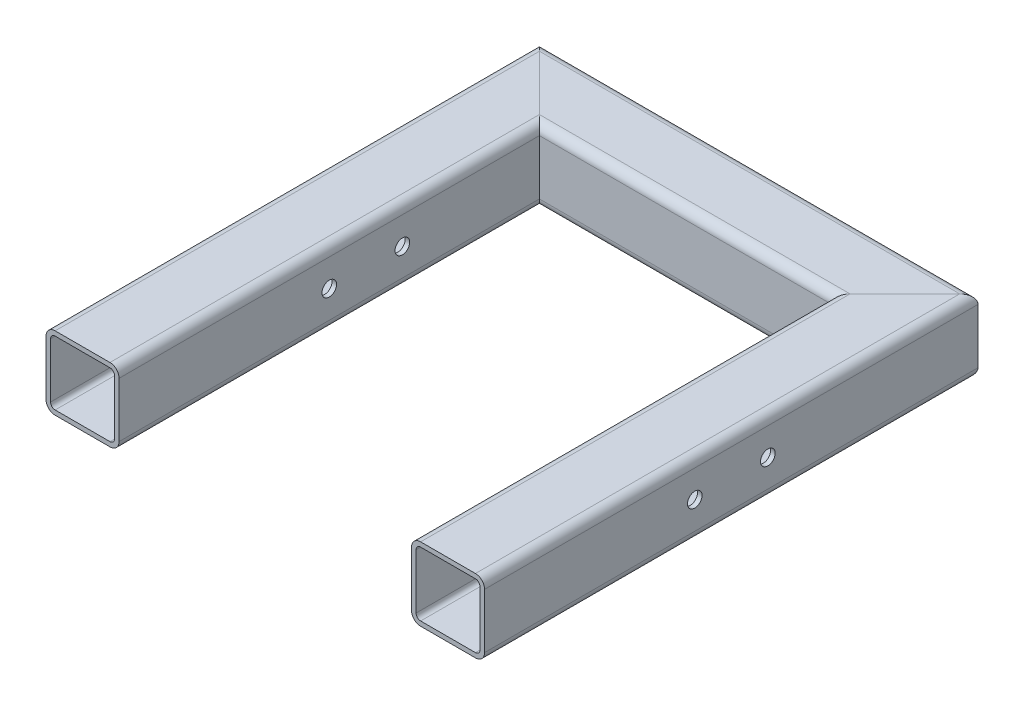
SolidWorks part; units mm, degrees
material "Chrome Stainless Steel"
ref_plane "Front Plane" through (0, 0, 0) normal (0, 0, 1) x (1, 0, 0)
ref_plane "Top Plane" through (0, 0, 0) normal (0, 1, 0) x (1, 0, 0)
ref_plane "Right Plane" through (0, 0, 0) normal (1, 0, 0) x (0, 0, -1)
sketch3d "3DSketch1"
  line L0 (0, 0, 0) -> (0, 0, -500)
  line L1 (0, 0, -500) -> (400, 0, -500)
  line L2 (400, 0, -500) -> (400, 0, 0)
  dimension "D1" = 400
  dimension "D2" = 500
  dimension "D3" = 500
other "Square tube 80 X 80 X 5(1)"
ref_plane "Plane1" through (0, 0, 0) normal (0, 0, -1) x (1, 0, 0)
sketch "Sketch1" plane through (0, 0, 0) normal (0, 0, -1) x (1, 0, 0)
  line L0 (-30, -35) -> (30, -35)
  line L1 (-35, -30) -> (-35, 30)
  line L2 (30, 35) -> (-30, 35)
  line L3 (35, 30) -> (35, -30)
  line L4 (-30, -40) -> (30, -40)
  line L5 (-40, -30) -> (-40, 30)
  line L6 (30, 40) -> (-30, 40)
  line L7 (40, 30) -> (40, -30)
  arc A0 (40, 30) -> (30, 40) centre (30, 30) ccw
  arc A1 (30, -40) -> (40, -30) centre (30, -30) ccw
  arc A2 (-40, -30) -> (-30, -40) centre (-30, -30) ccw
  arc A3 (-30, 40) -> (-40, 30) centre (-30, 30) ccw
  arc A4 (-30, 35) -> (-35, 30) centre (-30, 30) ccw
  arc A5 (35, 30) -> (30, 35) centre (30, 30) ccw
  arc A6 (30, -35) -> (35, -30) centre (30, -30) ccw
  arc A7 (-35, -30) -> (-30, -35) centre (-30, -30) ccw
  point P0 (-40, 0)
  point P1 (40, 0)
  point P2 (0, 40)
  point P3 (0, -40)
  point P4 (0, 0)
  point P5 (-40, -40)
  point P6 (40, -40)
  point P7 (40, 40)
  point P8 (-40, 40)
  point P33 (0, 0)
  dimension "D1" = 10
  dimension "Thickness" = 5
  dimension "V_leg" = 80
sketch "Sketch2" plane through (440, 0, 0) normal (1, 0, 0) x (0, 0, -1)
  line L0 (-44.976, 0) -> (664.8221, 0) construction
  line L1 (270, 260.4652) -> (270, -310.8873) construction
  circle A0 centre (230, 0) radius 8
  circle A1 centre (310, 0) radius 8
  dimension "D1" = 16
  dimension "D2" = 16
  dimension "D3" = 270
  dimension "D4" = 40
  dimension "D5" = 40
extrude "Cut-Extrude1" cut sketch "Sketch2" against normal up to surface (480 mm away)
